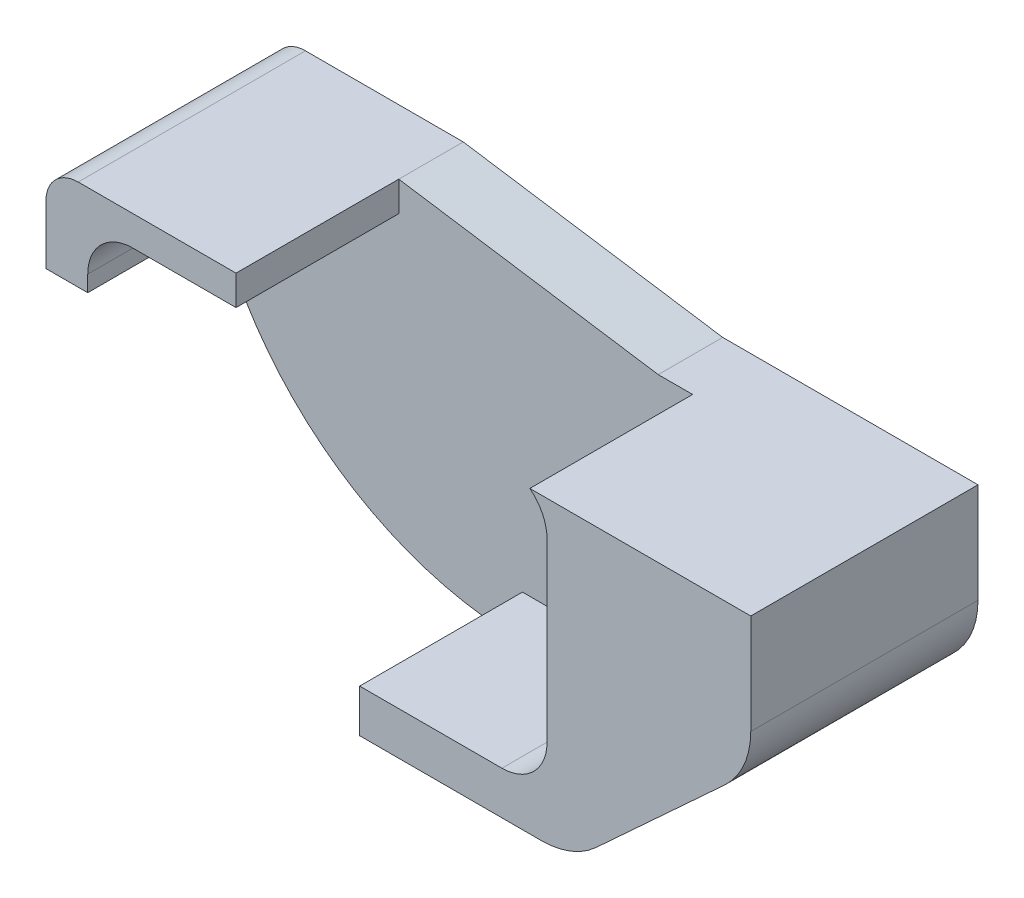
SolidWorks part; units mm, degrees
material "PET"
ref_plane "Front" through (0, 0, 0) normal (0, 0, 1) x (1, 0, 0)
ref_plane "Top" through (0, 0, 0) normal (0, 1, 0) x (1, 0, 0)
ref_plane "Right" through (0, 0, 0) normal (1, 0, 0) x (0, 0, -1)
ref_plane "Plane1" through (0, 0, 10.1) normal (0, 0, 1) x (1, 0, 0)
sketch "Sketch1" plane through (0, 0, 10.1) normal (0, 0, 1) x (1, 0, 0)
  line L0 (8.4239, 5.2576) -> (8.4239, -10.1112)
  line L1 (8.4239, -10.1112) -> (10.0227, -10.1112)
  line L2 (10.0227, -10.1112) -> (21.0645, 0.0572)
  line L3 (21.0645, 0.0572) -> (21.0645, 8.4576)
  line L4 (21.0645, 8.4576) -> (5.2239, 8.4576)
  arc A0 (5.2239, 8.4576) -> (8.4239, 5.2576) centre (5.2239, 5.2576) cw
extrude "Boss-Extrude1" add sketch "Sketch1" against normal blind 10.1
sketch "Sketch2" plane through (8.4239, 0, 0) normal (-1, 0, 0) x (0, 0, 1)
  line L0 (10.1, -10.1112) -> (0, -10.1112)
  line L1 (0, -10.1112) -> (0, -7.4424)
  line L2 (0, -7.4424) -> (10.1, -7.4424)
  line L3 (10.1, -7.4424) -> (10.1, -10.1112)
extrude "Boss-Extrude2" add sketch "Sketch2" along normal blind 11.6263
sketch "Sketch3" plane through (0, 0, 0) normal (0, 0, -1) x (-1, 0, 0)
  line L0 (3.2024, -10.1112) -> (-10.0227, -10.1112)
  line L1 (-10.0227, -10.1112) -> (-21.0645, 0.0572)
  line L2 (-21.0645, 0.0572) -> (-21.0645, 8.4576)
  line L3 (-21.0645, 8.4576) -> (-5.2239, 8.4576)
  line L4 (-5.2239, 8.4576) -> (10.8755, 10.9118)
  line L5 (10.8755, 10.9118) -> (22.6658, 10.9118)
  line L6 (22.6658, 10.9118) -> (22.6658, 5.2576)
  arc A0 (22.6658, 5.2576) -> (3.2024, -10.1112) centre (3.2024, 9.8977) cw
extrude "Boss-Extrude3" add sketch "Sketch3" along normal blind 4
sketch "Sketch4" plane through (0, 0, 0) normal (0, 0, 1) x (1, 0, 0)
  line L0 (-10.8755, 5.2576) -> (-22.6658, 5.2576)
  line L1 (-22.6658, 5.2576) -> (-22.6658, 10.9118)
  line L2 (-22.6658, 10.9118) -> (-10.8755, 10.9118)
  line L3 (-10.8755, 10.9118) -> (-10.8755, 5.2576)
extrude "Boss-Extrude4" add sketch "Sketch4" along normal blind 10.1
ref_plane "Plane2" through (0, 5.2576, 0) normal (0, -1, 0) x (1, 0, 0)
ref_plane "Plane3" through (0, 8.4576, 0) normal (0, 1, 0) x (1, 0, 0)
sketch "Sketch6" plane through (0, 8.4576, 0) normal (0, 1, 0) x (1, 0, 0)
  line L0 (-10.8755, -10.1) -> (-10.8755, 0)
  line L1 (-10.8755, 0) -> (-16.1761, 0)
  line L2 (-16.1761, 0) -> (-16.1761, -10.1)
  line L3 (-16.1761, -10.1) -> (-10.8755, -10.1)
extrude "Cut-Extrude1" cut sketch "Sketch6" against normal up to surface up to plane "Plane2"
hole_wizard "CBORE for #4 Binding Head Machine Screw1" positions "Sketch8" profile "Sketch7" counterbore size "#4" standard "ANSI Inch" end condition through all
sketch "Sketch8" plane through (0, 0, -4) normal (0, 0, -1) x (-1, 0, 0)
  line L0 (-8.4239, 5.2576) -> (-8.4239, -7.4424) construction
  line L1 (3.2024, -7.4424) -> (-8.4239, -7.4424) construction
  point P0 (-5.4239, -4.4424)
  dimension "D1" = 3
  dimension "D2" = 3
sketch "Sketch7" plane through (5.4239, -4.4424, -4) normal (1, 0, 0) x (0, 1, 0)
  line L0 (0, 0) -> (0, 14.1)
  line L1 (0, 14.1) -> (1.7, 14.1)
  line L3 (1.7, 14.1) -> (1.7, 2.4)
  line L4 (1.7, 2.4) -> (3, 2.4)
  line L5 (3, 2.4) -> (3, 0)
  line L7 (3, 0) -> (0, 0)
  line L11 (0, -6.35) -> (0, 107.95) construction
  dimension "Thru Hole Dia." = 3.4
  dimension "Thru Hole Depth" = 14.1
  dimension "C'Bore Dia." = 6
  dimension "C'Bore Depth" = 2.4
hole_wizard "CBORE for #4 Binding Head Machine Screw2" positions "Sketch10" profile "Sketch9" counterbore size "#4" standard "ANSI Inch" end condition up to next
sketch "Sketch10" plane through (0, 0, -4) normal (0, 0, -1) x (-1, 0, 0)
  circle A0 centre (-5.4239, -4.4424) radius 1.7 construction
  point P0 (17.0761, 6.0576)
  dimension "D1" = 10.5
  dimension "D2" = 22.5
sketch "Sketch9" plane through (-17.0761, 6.0576, -4) normal (1, 0, 0) x (0, 1, 0)
  line L0 (0, 0) -> (0, 14.1)
  line L1 (0, 14.1) -> (1.7272, 14.1)
  line L3 (1.7272, 14.1) -> (1.7272, 2.4)
  line L4 (1.7272, 2.4) -> (3, 2.4)
  line L5 (3, 2.4) -> (3, 0)
  line L7 (3, 0) -> (0, 0)
  line L11 (0, -6.35) -> (0, 107.95) construction
  dimension "Thru Hole Dia." = 3.4544
  dimension "Thru Hole Depth" = 14.1
  dimension "C'Bore Dia." = 6
  dimension "C'Bore Depth" = 2.4
fillet "Fillet1" radius 2 1 edges at (-22.6658, 10.9118, 3.05)
fillet "Fillet2" radius 3.2 1 edges at (8.4239, -7.4424, 5.05)
fillet "Fillet3" radius 5 2 edges at (21.0645, 0.0572, 3.05) (10.0227, -10.1112, 3.05)
sketch "Sketch11" plane through (0, 0, 10.1) normal (0, 0, 1) x (1, 0, 0)
  line L0 (-3.2024, -7.4424) -> (5.2239, -7.4424) construction
  line L1 (5.6239, -7.4424) -> (-20.0761, -7.4424)
  line L2 (8.4239, -4.6424) -> (8.4239, 6.2576)
  line L3 (5.6239, 9.0576) -> (-17.2761, 9.0576)
  line L4 (-20.0761, -7.4424) -> (-20.0761, 6.2576)
  line L5 (8.4239, 5.2576) -> (8.4239, -4.2424) construction
  arc A0 (-17.2761, 9.0576) -> (-20.0761, 6.2576) centre (-17.2761, 6.2576) ccw
  arc A1 (8.4239, -4.6424) -> (5.6239, -7.4424) centre (5.6239, -4.6424) cw
  arc A2 (5.6239, 9.0576) -> (8.4239, 6.2576) centre (5.6239, 6.2576) cw
  point P10 (-20.0761, 9.0576)
  point P13 (8.4239, -7.4424)
  dimension "D3" = 2.8
  dimension "D1" = 16.5
  dimension "D2" = 28.5
extrude "Cut-Extrude2" cut sketch "Sketch11" against normal up to surface (10.1 mm away) up to face at (-6.1944, 2.1145, 0)
